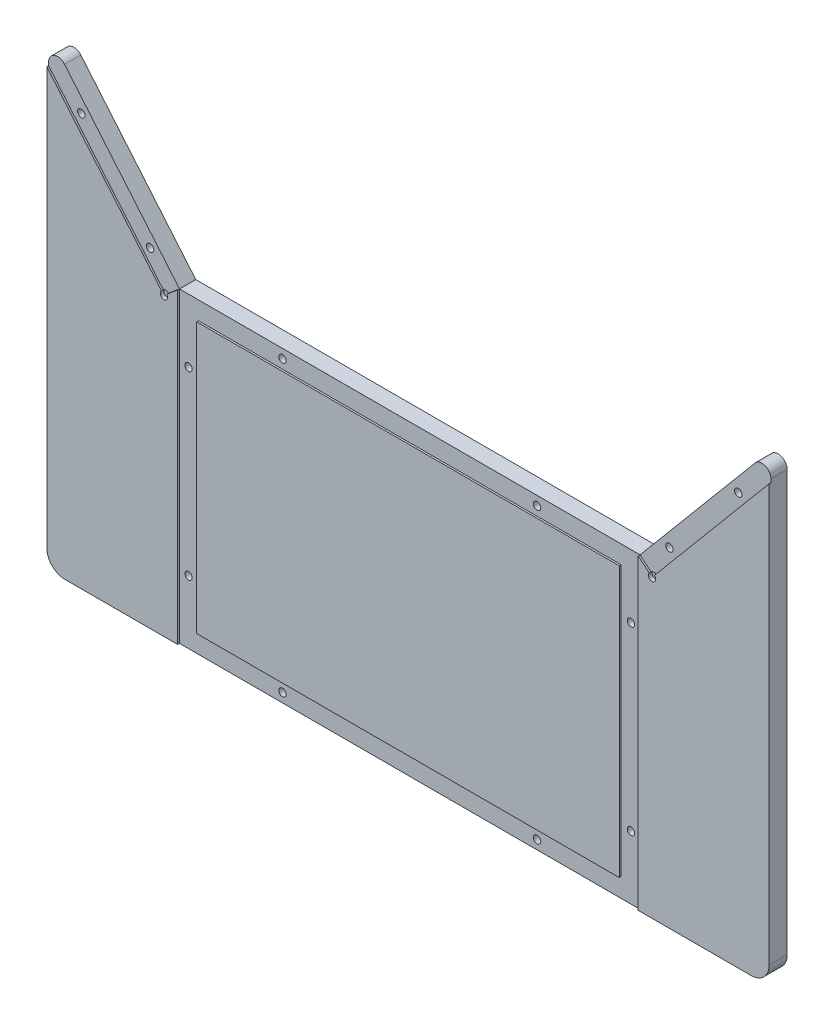
SolidWorks part; units mm, degrees
ref_plane "Front Plane" through (0, 0, 0) normal (0, 0, 1) x (1, 0, 0)
ref_plane "Top Plane" through (0, 0, 0) normal (0, 1, 0) x (1, 0, 0)
ref_plane "Right Plane" through (0, 0, 0) normal (1, 0, 0) x (0, 0, -1)
sketch "Sketch1" plane through (0, 0, 0) normal (0, 0, 1) x (1, 0, 0)
  line L11 (-200, 0) -> (200, 0)
  line L13 (200, 256.4021) -> (127.5, 170)
  line L14 (200, 170) -> (-96.2655, 170) construction
  line L15 (0, 0) -> (0, 312.6731) construction
  line L16 (127.5, 170) -> (-127.5, 170)
  line L17 (-200, 256.4021) -> (-127.5, 170)
  line L19 (200, 256.4021) -> (200, 170)
  line L20 (200, 170) -> (200, 0)
  line L21 (-200, 170) -> (-200, 0)
  line L22 (-200, 256.4021) -> (-200, 170)
  point P13 (0, 170)
  dimension "D1" = 255
  dimension "D2" = 170
  dimension "D4" = 140
extrude "Boss-Extrude2" add sketch "Sketch1" along normal blind 10
sketch "Esquisse2" plane through (0, 0, 10) normal (0, 0, 1) x (1, 0, 0)
  line L0 (-200, 0) -> (200, 0) construction
  line L1 (-127.5, 170) -> (127.5, 170)
  line L2 (-127.5, 170) -> (-127.5, 0)
  line L3 (-127.5, 0) -> (127.5, 0)
  line L4 (127.5, 170) -> (127.5, 0)
  line L6 (-117, 160) -> (117, 160)
  line L7 (-117, 160) -> (-117, 10.5)
  line L8 (-117, 10.5) -> (117, 10.5)
  line L9 (117, 160) -> (117, 10.5)
  dimension "D1" = 255
  dimension "D2" = 10
  dimension "D3" = 10.5
  dimension "D4" = 10.5
  dimension "D5" = 10.5
extrude "Enlèv. mat.-Extru.1" cut sketch "Esquisse2" against normal blind 1
sketch "Esquisse3" plane through (0, 0, 10) normal (0, 0, 1) x (1, 0, 0)
  line L0 (127.5, 170) -> (135.1604, 163.5721)
  line L1 (135.1604, 163.5721) -> (200, 240.8449)
  line L2 (200, 0) -> (200, 256.4021) construction
  line L3 (200, 240.8449) -> (200, 256.4021)
  line L4 (200, 256.4021) -> (127.5, 170)
  line L5 (0, 170) -> (0, 98.053) construction
  line L6 (127.5, 170) -> (-127.5, 170) construction
  line L7 (-200, 256.4021) -> (-127.5, 170)
  line L8 (-200, 240.8449) -> (-200, 256.4021)
  line L9 (-135.1604, 163.5721) -> (-200, 240.8449)
  line L10 (-127.5, 170) -> (-135.1604, 163.5721)
  dimension "D1" = 10
extrude "Enlèv. mat.-Extru.2" cut sketch "Esquisse3" against normal blind 1
fillet "Congé1" radius 10 1 edges at (200, 0, 5)
fillet "Congé2" radius 10 1 edges at (-200, 0, 5)
fillet "Congé3" radius 5 1 edges at (-200, 256.4021, 4.5)
fillet "Congé4" radius 5 1 edges at (200, 256.4021, 4.5)
sketch "Esquisse5" plane through (0, 0, 10) normal (0, 0, 1) x (1, 0, 0)
  line L0 (0, 170) -> (0, 115.3865) construction
  line L1 (127.5, 170) -> (-127.5, 170) construction
  circle A0 centre (-135.1604, 163.5721) radius 2
  circle A1 centre (135.1604, 163.5721) radius 2
  dimension "D1" = 4
extrude "Enlèv. mat.-Extru.3" cut sketch "Esquisse5" against normal blind 2
sketch "Esquisse6" plane through (0, 0, 0) normal (0, 0, -1) x (-1, 0, 0)
  line L0 (0, 170) -> (0, 0) construction
  line L1 (-127.5, 170) -> (127.5, 170) construction
  line L2 (-200, 85) -> (200, 85) construction
  line L3 (-200, 10) -> (-200, 242.6647) construction
  line L4 (200, 242.6647) -> (200, 10) construction
  line L6 (-127.5, 170) -> (-127.5, 0) construction
  line L7 (190, 0) -> (-190, 0) construction
  circle A2 centre (-70.5, 165) radius 2.05
  circle A3 centre (-122.5, 135) radius 2.05
  circle A4 centre (122.5, 135) radius 2.05
  circle A5 centre (70.5, 165) radius 2.05
  circle A6 centre (70.5, 5) radius 2.05
  circle A7 centre (122.5, 35) radius 2.05
  circle A8 centre (-122.5, 35) radius 2.05
  circle A9 centre (-70.5, 5) radius 2.05
  dimension "D1" = 4.1
  dimension "D2" = 4.1
  dimension "D3" = 5
  dimension "D4" = 57
  dimension "D5" = 35
  dimension "D6" = 5
extrude "Enlèv. mat.-Extru.4" cut sketch "Esquisse6" against normal blind 10
sketch "Esquisse7" plane through (0, 0, 0) normal (0, 0, -1) x (-1, 0, 0)
  line L0 (127.5, 170) -> (191.1698, 245.8787) construction
  line L1 (127.5, 170) -> (143.6792, 147.1515) construction
  line L2 (143.7778, 181.6206) -> (139.7105, 184.5519) construction
  line L3 (139.7105, 184.5519) -> (158.9941, 207.5332) construction
  line L4 (158.9941, 207.5332) -> (174.0619, 194.8899) construction
  line L5 (0, 170) -> (0, 130.8654) construction
  line L6 (-127.5, 170) -> (127.5, 170) construction
  line L7 (-158.9941, 207.5332) -> (-174.0619, 194.8899) construction
  line L8 (-139.7105, 184.5519) -> (-158.9941, 207.5332) construction
  line L9 (-143.7778, 181.6206) -> (-139.7105, 184.5519) construction
  line L10 (-126.5, 170) -> (-189.4441, 107.0559) construction
  circle A0 centre (143.7778, 181.6206) radius 2.05
  circle A1 centre (181.8709, 227.018) radius 2.05
  circle A2 centre (-181.8709, 227.018) radius 2.05
  circle A3 centre (-143.7778, 181.6206) radius 2.05
  dimension "D2" = 4.1
  dimension "D1" = 5
  dimension "D3" = 20
  dimension "D4" = 30
extrude "Enlèv. mat.-Extru.5" cut sketch "Esquisse7" against normal blind 10
